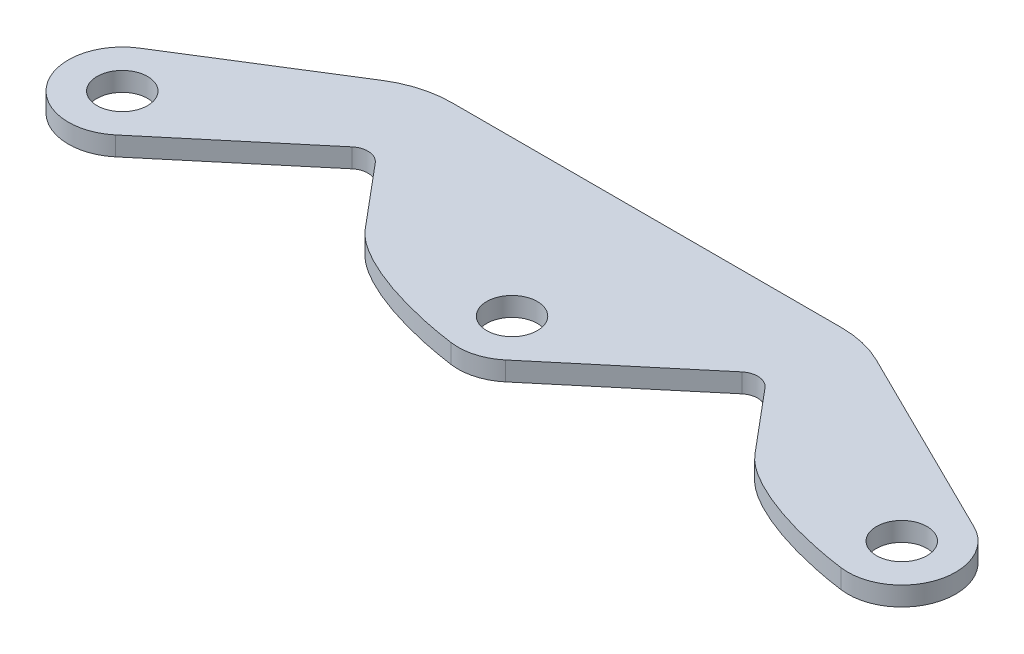
SolidWorks part; units mm, degrees
material "1100-H16 Rod (SS)"
ref_plane "Front Plane" through (0, 0, 0) normal (0, 0, 1) x (1, 0, 0)
ref_plane "Top Plane" through (0, 0, 0) normal (0, 1, 0) x (1, 0, 0)
ref_plane "Right Plane" through (0, 0, 0) normal (1, 0, 0) x (0, 0, -1)
sketch "Sketch1" plane through (0, 0, 0) normal (0, 1, 0) x (1, 0, 0)
  line L5 (-59.2149, -6.8944) -> (-37.7657, 11.1037)
  line L6 (0, 0) -> (-65, 0) construction
  line L12 (-105.1817, 0) -> (-30.986, 0) construction
  line L15 (-1.7463, 0) -> (1.7463, 0) construction
  line L16 (-24.7352, 0.2418) -> (-33.5392, 10.7339)
  line L18 (-25.9912, 3.6528) -> (25.9912, -3.6528) construction
  line L19 (-89.7352, 0.2418) -> (-98.5392, 10.7339)
  line L20 (-124.2149, -6.8944) -> (-102.7657, 11.1037)
  line L21 (-134.7728, 7.6302) -> (-109.8526, 23.2182)
  line L22 (-100.8373, 25.8055) -> (-35.8373, 25.8055)
  line L23 (-28.2985, 24.0425) -> (3.9911, 8.0667)
  circle A0 centre (0, 0) radius 4.2164
  circle A3 centre (-65, 0) radius 4.2164
  circle A4 centre (-130, 0) radius 4.2164
  arc A6 (-134.7728, 7.6302) -> (-124.2149, -6.8944) centre (-130, 0) ccw
  arc A8 (-66.2526, -8.9124) -> (-59.2149, -6.8944) centre (-65, 0) ccw
  arc A9 (-1.2526, -8.9124) -> (3.9911, 8.0667) centre (0, 0) ccw
  arc A10 (-33.5392, 10.7339) -> (-37.7657, 11.1037) centre (-35.8373, 8.8055) ccw
  arc A16 (-98.5392, 10.7339) -> (-102.7657, 11.1037) centre (-100.8373, 8.8055) ccw
  arc A17 (-109.8526, 23.2182) -> (-100.8373, 25.8055) centre (-100.8373, 8.8055) cw
  arc A18 (-35.8373, 25.8055) -> (-28.2985, 24.0425) centre (-35.8373, 8.8055) cw
  ellipse E0 centre (-65, 0) end of major axis (-90.9912, 3.6528) minor radius 9 (-89.7352, 0.2418) -> (-66.2526, -8.9124) ccw
  ellipse E1 centre (0, 0) end of major axis (-25.9912, 3.6528) minor radius 9 (-24.7352, 0.2418) -> (-1.2526, -8.9124) ccw
  dimension "D2" = 8.4328
  dimension "D3" = 9
  dimension "D4" = 40
  dimension "D5" = 3
  dimension "D7" = 28
  dimension "D8" = 8
  dimension "D9" = 14
  dimension "D11" = 14
  dimension "D1" = 65
  dimension "D6" = 2
  dimension "D10" = 3
extrude "Boss-Extrude1" add sketch "Sketch1" along normal blind 3.175
